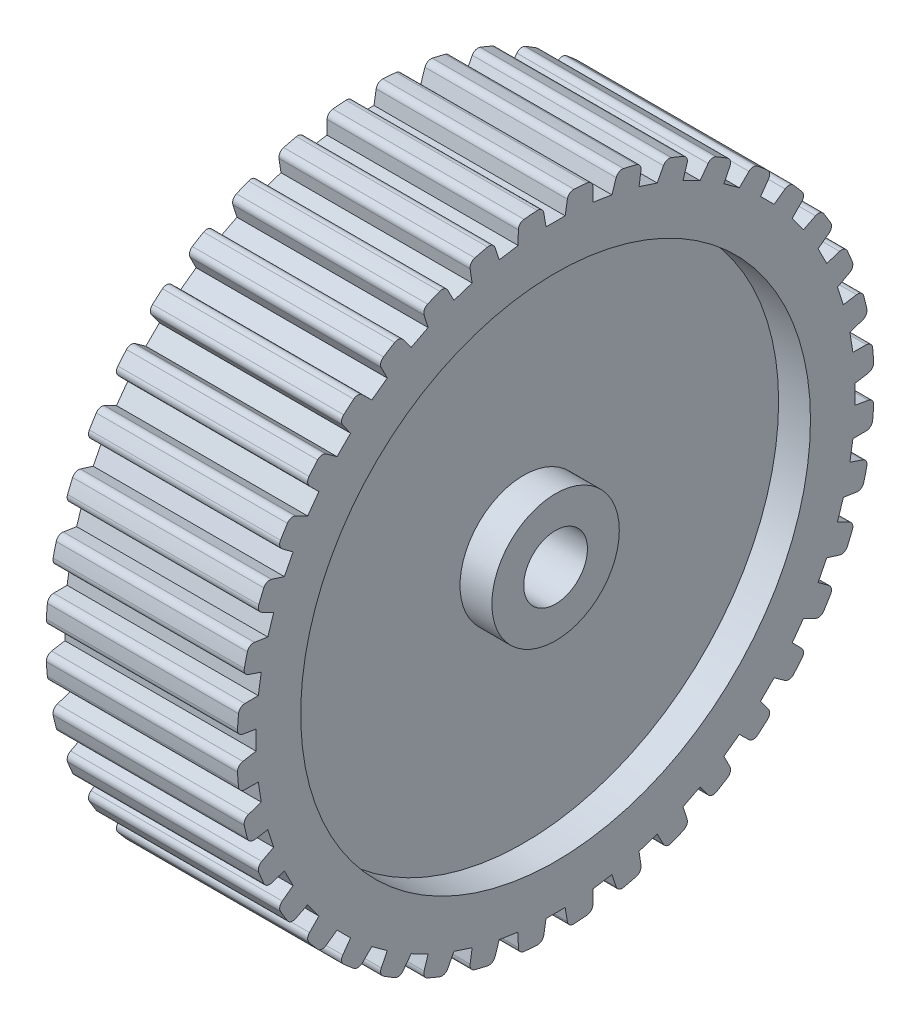
SolidWorks part; units mm, degrees
ref_plane "Front Plane" through (0, 0, 0) normal (0, 0, 1) x (1, 0, 0)
ref_plane "Top Plane" through (0, 0, 0) normal (0, 1, 0) x (1, 0, 0)
ref_plane "Right Plane" through (0, 0, 0) normal (1, 0, 0) x (0, 0, -1)
sketch "Sketch1" plane through (0, 0, 0) normal (0, 0, 1) x (1, 0, 0)
  line L0 (0, 0) -> (-34.486, 0) construction
  line L1 (0, 5) -> (-30, 5)
  line L2 (-30, 5) -> (-30, 10)
  line L3 (-30, 10) -> (-25, 10)
  line L4 (-25, 10) -> (-25, 40)
  line L5 (-25, 40) -> (-30, 40)
  line L6 (-30, 40) -> (-30, 50)
  line L7 (-30, 50) -> (0, 50)
  line L8 (0, 50) -> (0, 40)
  line L9 (0, 40) -> (-5, 40)
  line L10 (-5, 40) -> (-5, 10)
  line L11 (-5, 10) -> (0, 10)
  line L12 (0, 10) -> (0, 5)
  dimension "D1" = 10
  dimension "D2" = 100
  dimension "D3" = 30
  dimension "D4" = 20
  dimension "D5" = 5
  dimension "D6" = 10
revolve "Revolve1" add sketch "Sketch1" angle 360 about L0
sketch "Sketch2" plane through (0, 0, 0) normal (1, 0, 0) x (0, 0, -1)
  line L0 (-2.5, 53) -> (-1.5, 47)
  line L1 (-1.5, 47) -> (1.5, 47)
  line L2 (1.5, 47) -> (2.5, 53)
  line L3 (2.5, 53) -> (-2.5, 53)
  circle A0 centre (0, 0) radius 50 construction
  point P2 (0, 47)
  point P5 (0, 53)
  point P7 (0, 50)
  dimension "D1" = 3
  dimension "D2" = 5
  dimension "D3" = 6
  dimension "D4" = 3
extrude "Cut-Extrude1" cut sketch "Sketch2" against normal blind 44
fillet "Fillet1" radius 1 2 edges at (-15, 49.9602, 1.9934) (-15, 49.9602, -1.9934)
pattern_circular "CirPattern1" count 40 over 360 about axis through (0, 0, 0) along (1, 0, 0) of "Cut-Extrude1", "Fillet1"
